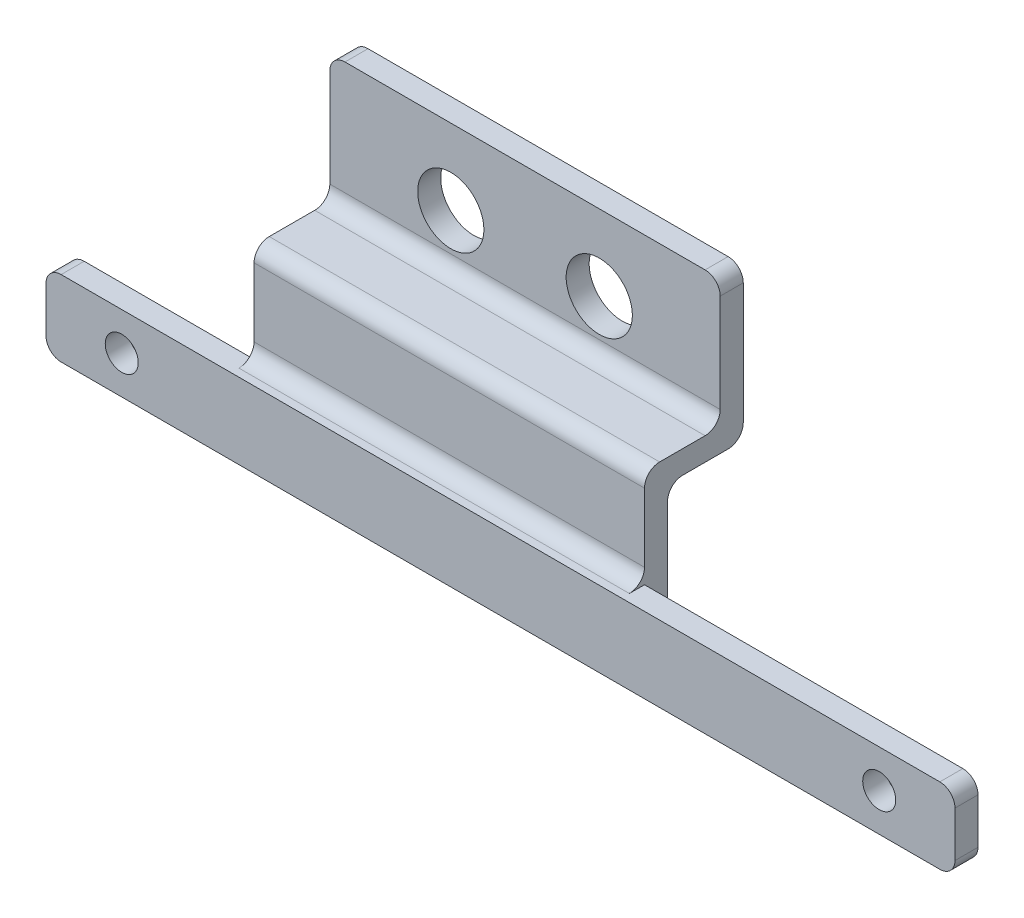
SolidWorks part; units mm, degrees
material "1060 Alloy"
ref_plane "Front" through (0, 0, 0) normal (0, 0, 1) x (1, 0, 0)
ref_plane "Top" through (0, 0, 0) normal (0, 1, 0) x (1, 0, 0)
ref_plane "Right" through (0, 0, 0) normal (1, 0, 0) x (0, 0, -1)
sketch "Sketch1" plane through (0, 0, 0) normal (0, 0, 1) x (1, 0, 0)
  line L0 (-12.885, 5) -> (12.885, 5)
  line L1 (12.885, 5) -> (12.885, -5)
  line L2 (-12.885, 5) -> (-12.885, -5)
  line L3 (-12.885, -5) -> (12.885, -5)
  line L4 (0, 5) -> (0, -5) construction
  line L5 (-4.9, 0) -> (4.9, 0) construction
  line L6 (-12.885, 0) -> (12.885, 0) construction
  circle A0 centre (-4.9, 0) radius 2.185
  circle A1 centre (4.9, 0) radius 2.185
  point P12 (0, 0)
  dimension "D1" = 4.37
  dimension "D2" = 9.8
  dimension "D3" = 4.9
  dimension "D4" = 10
  dimension "D5" = 25.77
extrude "Boss-Extrude1" add sketch "Sketch1" along normal blind 1.52
ref_plane "Plane1" through (0, 0, 1.52) normal (0, 0, 1) x (1, 0, 0)
sketch "Sketch2" plane through (0, 0, 1.52) normal (0, 0, 1) x (1, 0, 0)
  line L0 (-12.885, -5) -> (-12.885, -3.48)
  line L1 (-12.885, 5) -> (-12.885, -5) construction
  line L2 (-12.885, -3.48) -> (12.885, -3.48)
  line L3 (12.885, -5) -> (12.885, 5) construction
  line L4 (12.885, -3.48) -> (12.885, -5)
  line L5 (-12.885, -5) -> (12.885, -5)
  dimension "D1" = 1.52
extrude "Boss-Extrude2" add sketch "Sketch2" along normal blind 5
ref_plane "Plane2" through (0, -5, 0) normal (0, -1, 0) x (-1, 0, 0)
sketch "Sketch3" plane through (0, -5, 0) normal (0, -1, 0) x (-1, 0, 0)
  line L0 (-12.885, -6.52) -> (12.885, -6.52)
  line L1 (12.885, -6.52) -> (12.885, -5)
  line L2 (12.885, -6.52) -> (12.885, 0) construction
  line L3 (12.885, -5) -> (-12.885, -5)
  line L4 (-12.885, -6.52) -> (-12.885, 0) construction
  line L5 (-12.885, -5) -> (-12.885, -6.52)
  dimension "D1" = 1.52
extrude "Boss-Extrude3" add sketch "Sketch3" along normal blind 10
ref_plane "Plane3" through (0, 0, 6.52) normal (0, 0, 1) x (1, 0, 0)
sketch "Sketch4" plane through (0, 0, 6.52) normal (0, 0, 1) x (1, 0, 0)
  line L0 (-12.885, -15) -> (-25.1, -15)
  line L1 (-25.1, -15) -> (-25.1, -10)
  line L2 (-25.1, -10) -> (34.9, -10)
  line L3 (34.9, -10) -> (34.9, -15)
  line L4 (34.9, -15) -> (-12.885, -15)
  line L5 (0, 5) -> (0, -15) construction
  line L6 (12.885, 5) -> (-12.885, 5) construction
  dimension "D1" = 60
  dimension "D2" = 25.1
  dimension "D3" = 5
extrude "Boss-Extrude4" add sketch "Sketch4" along normal blind 1.52
sketch "Sketch5" plane through (0, 0, 6.52) normal (0, 0, 1) x (1, 0, 0)
  line L0 (-25.1, -12.5) -> (34.9, -12.5) construction
  line L1 (-25.1, -10) -> (-25.1, -15) construction
  line L2 (34.9, -15) -> (34.9, -10) construction
  line L4 (-25.1, -15) -> (34.9, -15) construction
  line L5 (4.9, -10) -> (4.9, -15) construction
  line L6 (34.9, -10) -> (-25.1, -10) construction
  circle A0 centre (-20.1, -12.5) radius 1.09
  circle A1 centre (29.9, -12.5) radius 1.09
  dimension "D1" = 2.18
  dimension "D2" = 25
extrude "Cut-Extrude1" cut sketch "Sketch5" against normal mid plane 10
fillet "Fillet1" radius 1 12 edges at (0, -5, 0) (-25.1, -15, 7.28) (-25.1, -10, 7.28) (34.9, -15, 7.28) (34.9, -10, 7.28) (0, -10, 6.52) (0, -3.48, 6.52) (-12.885, 5, 0.76) (12.885, 5, 0.76) (0, -15, 5)
